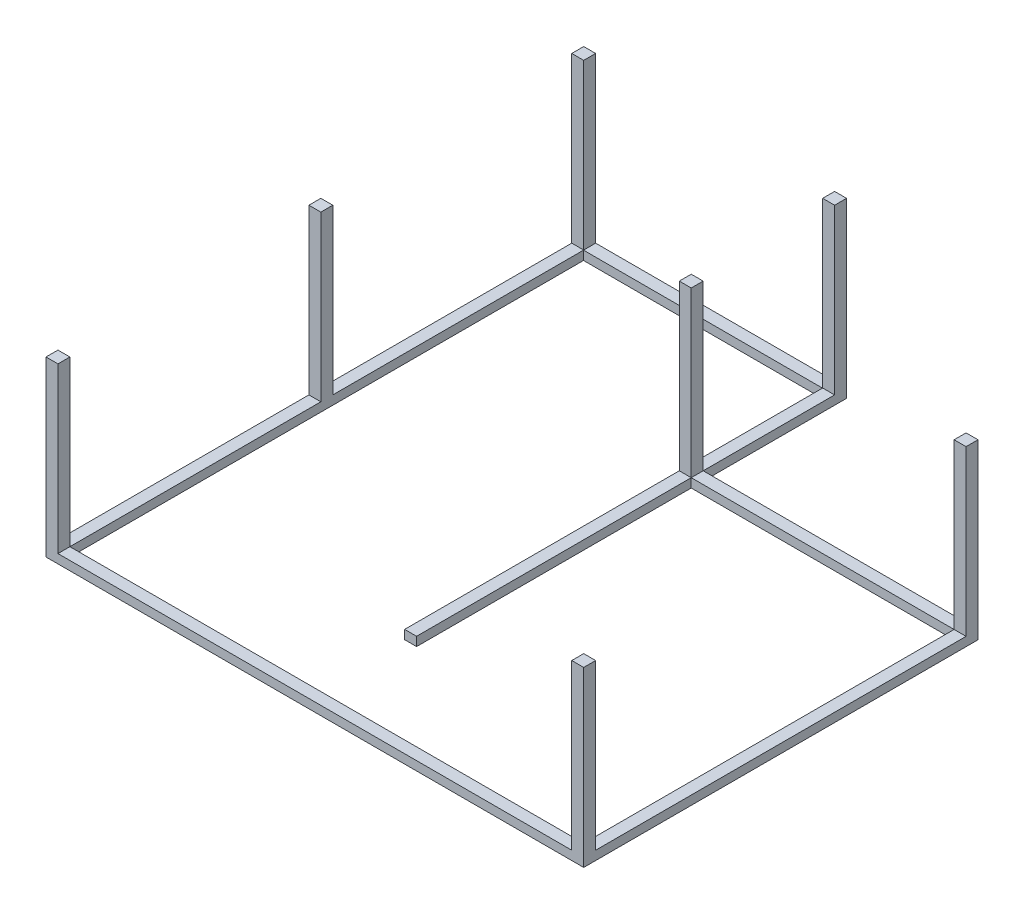
SolidWorks part; units mm, degrees
ref_plane "Спереди" through (0, 0, 0) normal (0, 0, 1) x (1, 0, 0)
ref_plane "Сверху" through (0, 0, 0) normal (0, 1, 0) x (1, 0, 0)
ref_plane "Справа" through (0, 0, 0) normal (1, 0, 0) x (0, 0, -1)
sketch "Эскиз1" plane through (0, 0, 0) normal (0, -1, 0) x (1, 0, 0)
  line L0 (0, 0) -> (9000, 0)
  line L1 (9000, 0) -> (9000, -6600)
  line L2 (9000, -6600) -> (4400, -6600)
  line L3 (4200, -1803) -> (4200, -6397) construction
  line L4 (4400, -6600) -> (4400, -9000)
  line L5 (4400, -9000) -> (0, -9000)
  line L6 (0, -9000) -> (0, 0)
  line L7 (200, -200) -> (8800, -200)
  line L10 (4200, -8797) -> (200, -8797)
  line L11 (200, -8797) -> (200, -200)
  line L12 (8800, -200) -> (8800, -6400)
  line L22 (4400, -6400) -> (8800, -6400)
  line L23 (4500, -200) -> (8800, -200) construction
  line L24 (8800, -203) -> (8800, -6400) construction
  line L25 (8797, -6600) -> (4400, -6600) construction
  line L26 (8797, -6400) -> (4400, -6400) construction
  line L27 (4400, -6600) -> (9000, -6600) construction
  line L28 (4400, -8797) -> (4400, -6603) construction
  line L29 (4400, -6400) -> (4400, -1803)
  line L30 (4400, -1803) -> (4200, -1803)
  line L31 (4200, -1803) -> (4200, -8797)
  line L32 (4200, -8797) -> (4200, -6603) construction
  line L34 (0, -9000) -> (4400, -9000) construction
  line L35 (3597.5552, -8797) -> (2379.0159, -8797) construction
  point P2 (0, 0)
  point P5 (0, 0)
  point P10 (4200, -3740.5149)
  point P19 (4400, -1807.9095)
  point P20 (4400, -1803)
  dimension "D1" = 200
  dimension "D2" = 200
  dimension "D3" = 200
extrude "Бобышка-Вытянуть1" add sketch "Эскиз1" along normal blind 150
sketch "Эскиз2" plane through (0, 0, 0) normal (0, 1, 0) x (1, 0, 0)
  line L1 (0, 9000) -> (200, 9000)
  line L2 (0, 9000) -> (0, 8800)
  line L3 (0, 8800) -> (200, 8800)
  line L4 (200, 9000) -> (200, 8800)
  line L7 (4200, 8797) -> (4200, 1803) construction
  line L8 (4400, 9000) -> (4200, 9000)
  line L9 (4400, 9000) -> (4400, 8800)
  line L10 (4400, 8800) -> (4200, 8800)
  line L11 (4200, 9000) -> (4200, 8800)
  line L12 (4400, 6600) -> (4200, 6600)
  line L13 (4400, 6600) -> (4400, 6400)
  line L14 (4400, 6400) -> (4200, 6400)
  line L15 (4200, 6600) -> (4200, 6400)
  line L17 (4400, 6400) -> (8800, 6400) construction
  line L19 (0, 0) -> (0, 9000) construction
  line L20 (9000, 6600) -> (8800, 6600)
  line L21 (9000, 6600) -> (9000, 6400)
  line L22 (9000, 6400) -> (8800, 6400)
  line L23 (8800, 6600) -> (8800, 6400)
  line L24 (9000, 0) -> (8800, 0)
  line L25 (9000, 0) -> (9000, 200)
  line L26 (9000, 200) -> (8800, 200)
  line L27 (8800, 0) -> (8800, 200)
  line L28 (0, 0) -> (200, 0)
  line L29 (0, 0) -> (0, 200)
  line L30 (0, 200) -> (200, 200)
  line L31 (200, 0) -> (200, 200)
  line L32 (0, 4600) -> (200, 4600)
  line L33 (0, 4600) -> (0, 4400)
  line L34 (0, 4400) -> (200, 4400)
  line L35 (200, 4600) -> (200, 4400)
  line L36 (0, 4600) -> (200, 4600) construction
  line L37 (200, 200) -> (200, 8797) construction
  line L39 (0, 4400) -> (200, 4400) construction
  dimension "D1" = 200
extrude "Бобышка-Вытянуть2" add sketch "Эскиз2" along normal up to surface (2750 mm away)
